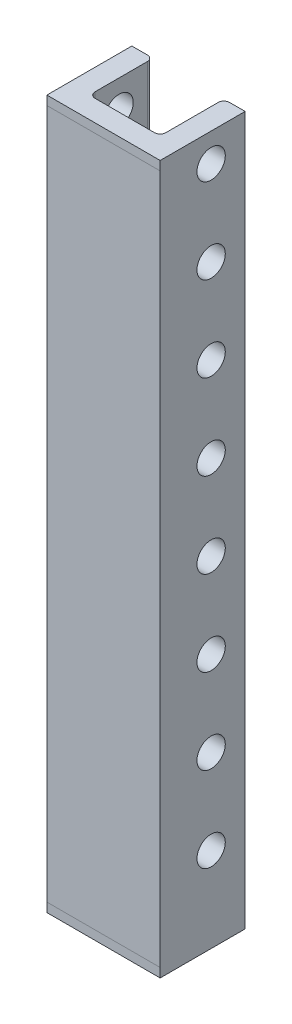
SolidWorks part; units mm, degrees
material "Plain Carbon Steel"
ref_plane "Front Plane" through (0, 0, 0) normal (0, 0, 1) x (1, 0, 0)
ref_plane "Top Plane" through (0, 0, 0) normal (0, 1, 0) x (1, 0, 0)
ref_plane "Right Plane" through (0, 0, 0) normal (1, 0, 0) x (0, 0, -1)
sketch "Sketch1" plane through (0, 0, 0) normal (0, 1, 0) x (1, 0, 0)
  line L0 (0, 0) -> (50.8, 0) construction
  line L1 (0, 0) -> (0, 9.525) construction
  line L2 (50.8, 0) -> (50.8, 9.525) construction
  line L3 (0, 9.525) -> (50.8, 9.525) construction
  line L4 (0, 0) -> (0, 38.1) construction
  line L5 (0, 38.1) -> (9.525, 38.1) construction
  line L6 (9.525, 38.1) -> (9.525, 9.525) construction
  line L7 (9.525, 9.525) -> (41.275, 9.525) construction
  line L8 (41.275, 9.525) -> (41.275, 38.1) construction
  line L9 (41.275, 38.1) -> (50.8, 38.1) construction
  line L10 (50.8, 38.1) -> (50.8, 9.525) construction
  line L11 (0, 0) -> (50.8, 0)
  line L12 (50.8, 0) -> (50.8, 38.1)
  line L13 (50.8, 38.1) -> (41.275, 38.1)
  line L14 (41.275, 38.1) -> (41.275, 9.525)
  line L15 (41.275, 9.525) -> (9.525, 9.525)
  line L16 (9.525, 9.525) -> (9.525, 38.1)
  line L17 (9.525, 38.1) -> (0, 38.1)
  line L18 (0, 38.1) -> (0, 0)
  dimension "D1" = 50.8
  dimension "D2" = 9.525
  dimension "D3" = 38.1
  dimension "D4" = 9.525
  dimension "D5" = 9.525
  dimension "D6" = 9.525
extrude "Boss-Extrude1" add sketch "Sketch1" along normal blind 317.5 contours L15 L16 L17 L18 L11 L12 L13 L14
sketch "Sketch2" plane through (50.8, 0, 0) normal (1, 0, 0) x (0, 0, -1)
  line L0 (22.86, 317.5) -> (22.86, 0) construction
  line L1 (0, 0) -> (38.1, 0) construction
  line L3 (22.86, 158.75) -> (0, 158.75) construction
  line L4 (0, 317.5) -> (0, 0) construction
  line L5 (0, 158.75) -> (38.1, 158.75) construction
  line L6 (38.1, 317.5) -> (38.1, 0) construction
  line L8 (0, 317.5) -> (38.1, 317.5) construction
  circle A0 centre (22.86, 304.8) radius 6.35
  circle A1 centre (22.86, 190.5) radius 6.35
  circle A2 centre (22.86, 228.6) radius 6.35
  circle A3 centre (22.86, 266.7) radius 6.35
  circle A4 centre (22.86, 76.2) radius 6.35
  circle A5 centre (22.86, 38.1) radius 6.35
  circle A7 centre (22.86, 152.4) radius 6.35
  circle A8 centre (22.86, 114.3) radius 6.35
  dimension "D2" = 38.1
  dimension "D5" = 12.7
  dimension "D6" = 12.7
  dimension "D7" = 12.7
  dimension "D8" = 38.1
  dimension "D11" = 12.7
  dimension "D12" = 12.7
  dimension "D13" = 12.7
  dimension "D15" = 12.7
  dimension "D16" = 12.7
  dimension "D3" = 38.1
  dimension "D4" = 38.1
  dimension "D9" = 15.24
  dimension "D10" = 38.1
  dimension "D14" = 38.1
  dimension "D17" = 38.1
  dimension "D18" = 38.1
  dimension "D19" = 38.1
extrude "Cut-Extrude1" cut sketch "Sketch2" against normal blind 304.8
fillet "Fillet1" radius 2.54 4 edges at (41.275, 158.75, -9.525) (9.525, 158.75, -38.1) (41.275, 158.75, -38.1) (9.525, 158.75, -9.525)
sketch "Sketch3" plane through (0, 0, 0) normal (0, 0, 1) x (1, 0, 0)
  line L0 (50.8, 317.5) -> (0, 317.5)
  line L1 (50.8, 317.5) -> (50.8, 313.4449)
  line L2 (0, 317.5) -> (0, 313.4449)
  line L3 (50.8, 313.4449) -> (0, 313.4449)
split line "Split Line1"
sketch "Sketch4" plane through (0, 0, 0) normal (0, 0, 1) x (1, 0, 0)
  line L0 (0, 0) -> (50.8, 0)
  line L1 (0, 0) -> (0, 4.0879)
  line L2 (50.8, 0) -> (50.8, 4.0879)
  line L3 (0, 4.0879) -> (50.8, 4.0879)
split line "Split Line3"
